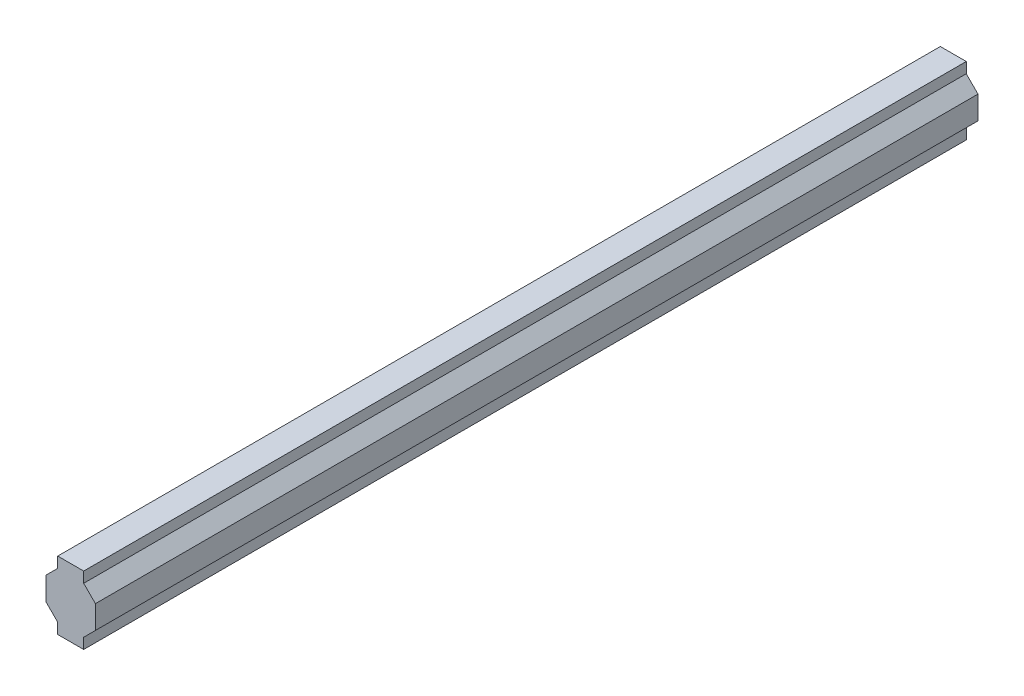
SolidWorks part; units mm, degrees
ref_plane "Front Plane" through (0, 0, 0) normal (0, 0, 1) x (1, 0, 0)
ref_plane "Top Plane" through (0, 0, 0) normal (0, 1, 0) x (1, 0, 0)
ref_plane "Right Plane" through (0, 0, 0) normal (1, 0, 0) x (0, 0, -1)
sketch "Sketch1" plane through (0, 0, 116.1066) normal (0, 0, 1) x (1, 0, 0)
  line L0 (-39.5503, 5.2942) -> (-36.8896, 7.9549)
  line L1 (-36.8896, 7.9549) -> (-36.8896, 10.362)
  line L2 (-36.8896, 10.362) -> (-31.011, 10.362)
  line L3 (-31.011, 7.9549) -> (-28.3503, 5.2942)
  line L4 (-28.3503, 5.2942) -> (-28.3503, 0.0298)
  line L5 (-28.3503, 0.0298) -> (-31.011, -2.6309)
  line L6 (-31.011, -2.6309) -> (-31.011, -5.038)
  line L7 (-31.011, -5.038) -> (-36.8896, -5.038)
  line L8 (-36.8896, -5.038) -> (-36.8896, -2.6309)
  line L9 (-36.8896, -2.6309) -> (-39.5503, 0.0298)
  line L10 (-39.5503, 0.0298) -> (-39.5503, 5.2942)
  line L11 (-31.011, 10.362) -> (-31.011, 7.9549)
  line L12 (-37.3896, 10.862) -> (-30.511, 10.862) construction
  line L13 (-37.3896, -5.538) -> (-30.511, -5.538) construction
  line L14 (-27.8503, 5.4185) -> (-27.8503, -0.0945) construction
  line L15 (-40.0503, 5.4185) -> (-40.0503, -0.0945) construction
  line L16 (-39.9917, 5.5599) -> (-37.3896, 8.162) construction
  line L17 (-37.3896, 8.162) -> (-37.3896, 10.862) construction
  line L18 (-30.511, 8.162) -> (-30.511, 10.862) construction
  line L19 (-27.9089, 5.5599) -> (-30.511, 8.162) construction
  line L20 (-27.9089, -0.2359) -> (-30.511, -2.838) construction
  line L21 (-30.511, -2.838) -> (-30.511, -5.538) construction
  line L22 (-37.3896, -2.838) -> (-37.3896, -5.538) construction
  line L23 (-39.9917, -0.2359) -> (-37.3896, -2.838) construction
  point P24 (-37.3896, 9.512)
  dimension "D1" = 0.5
  dimension "D2" = 0.5
  dimension "D3" = 0.5
  dimension "D4" = 0.5
  dimension "D5" = 0.5
  dimension "D6" = 0.5
  dimension "D7" = 0.5
  dimension "D8" = 0.5
  dimension "D9" = 0.5
  dimension "D10" = 0.5
  dimension "D11" = 0.5
  dimension "D12" = 0.5
extrude "Boss-Extrude1" add sketch "Sketch1" along normal blind 200
